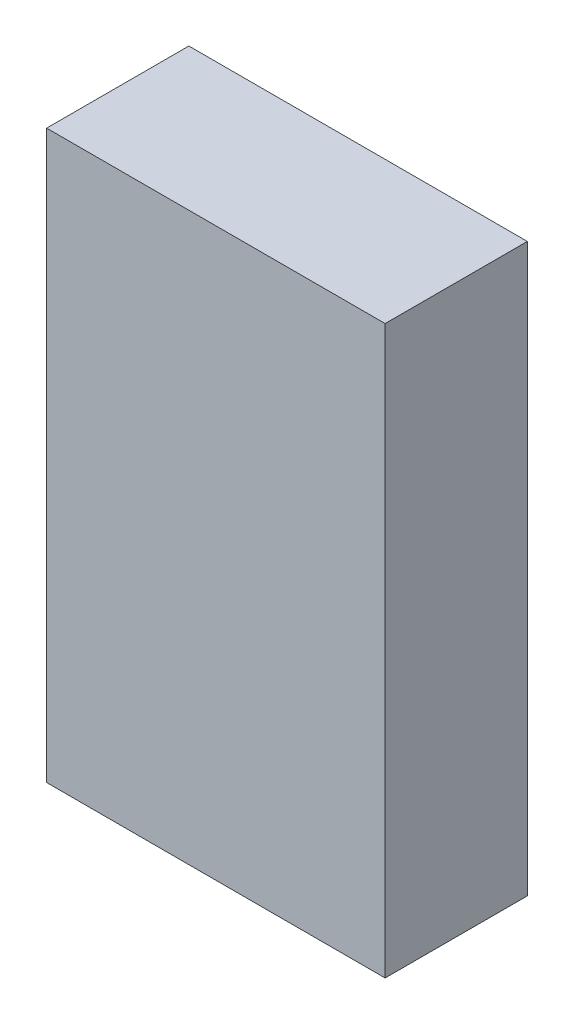
SolidWorks part; units mm, degrees
ref_plane "Front Plane" through (0, 0, 0) normal (0, 0, 1) x (1, 0, 0)
ref_plane "Top Plane" through (0, 0, 0) normal (0, 1, 0) x (1, 0, 0)
ref_plane "Right Plane" through (0, 0, 0) normal (1, 0, 0) x (0, 0, -1)
sketch "Sketch1" plane through (0, 0, 0) normal (0, 0, 1) x (1, 0, 0)
  line L1 (54.61, -91.44) -> (-54.61, -91.44)
  line L2 (54.61, -91.44) -> (54.61, 91.44)
  line L3 (54.61, 91.44) -> (-54.61, 91.44)
  line L4 (-54.61, -91.44) -> (-54.61, 91.44)
  line L5 (54.61, -91.44) -> (-54.61, 91.44) construction
  line L6 (54.61, 91.44) -> (-54.61, -91.44) construction
  point P0 (0, 0)
  dimension "D1" = 109.22
  dimension "D2" = 182.88
extrude "Boss-Extrude1" add sketch "Sketch1" along normal blind 45.8926
